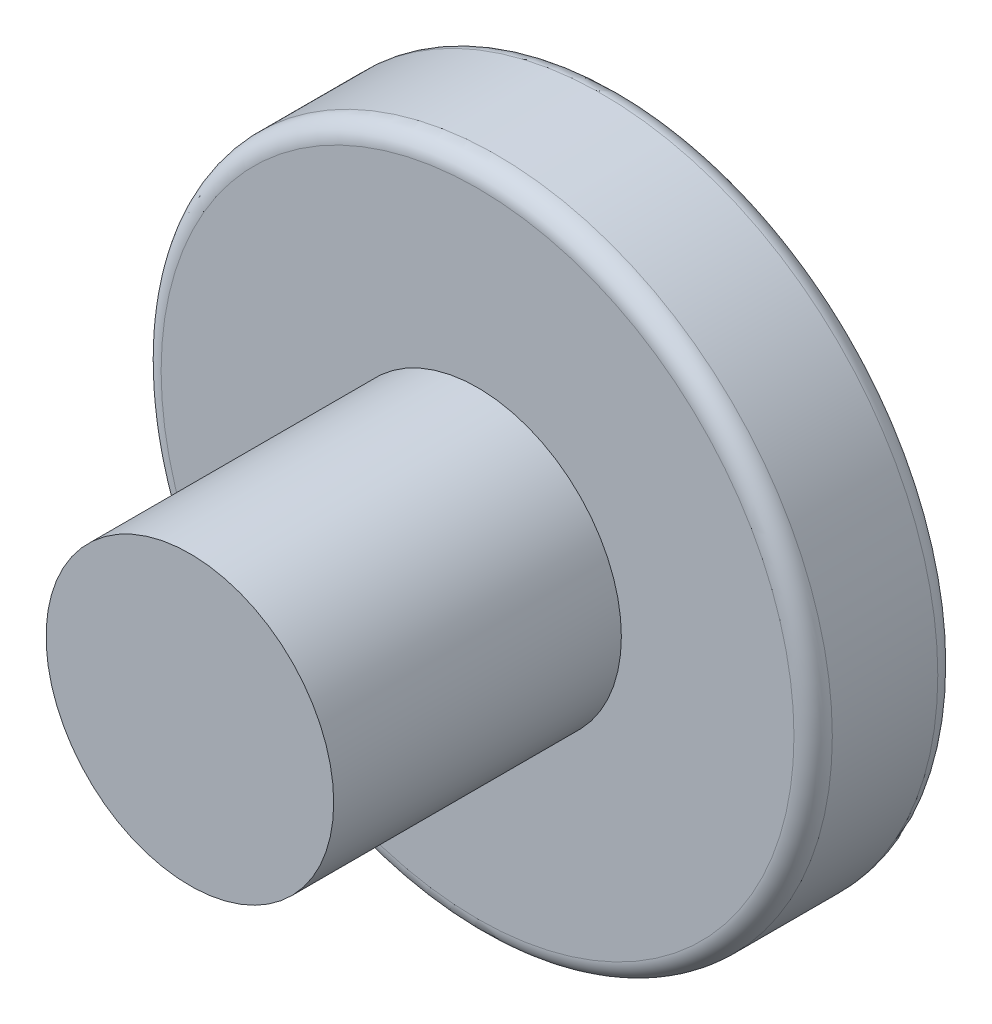
SolidWorks part; units mm, degrees
material "AISI 304"
ref_plane "前视基准面" through (0, 0, 0) normal (0, 0, 1) x (1, 0, 0)
ref_plane "上视基准面" through (0, 0, 0) normal (0, 1, 0) x (1, 0, 0)
ref_plane "右视基准面" through (0, 0, 0) normal (1, 0, 0) x (0, 0, -1)
other "Configuration Table"
sketch "草图1" plane through (0, 0, 0) normal (0, 0, 1) x (1, 0, 0)
  circle A0 centre (0, 0) radius 3.5
  dimension "D1" = 7
extrude "凸台-拉伸1" add sketch "草图1" along normal blind 1.5
sketch "草图2" plane through (0, 0, 1.5) normal (0, 0, 1) x (1, 0, 0)
  circle A1 centre (0, 0) radius 1.5
  dimension "D2" = 3
extrude "凸台-拉伸2" add sketch "草图2" along normal blind 3
fillet "圆角1" radius 0.2 2 edges at (3.5, 0, 0) (3.5, 0, 1.5)
sketch "草图3" plane through (0, 0, 0) normal (0, 0, -1) x (-1, 0, 0)
  line L0 (0, 0) -> (1.1547, 0) construction
  line L1 (1.1547, 0) -> (0.5774, 1)
  line L2 (0.5774, 1) -> (-0.5774, 1)
  line L3 (-0.5774, 1) -> (-1.1547, 0)
  line L4 (-1.1547, 0) -> (-0.5774, -1)
  line L5 (-0.5774, -1) -> (0.5774, -1)
  line L6 (0.5774, -1) -> (1.1547, 0)
  circle A0 centre (0, 0) radius 1 construction
  dimension "D1" = 2
extrude "切除-拉伸1" cut sketch "草图3" against normal blind 1.5
